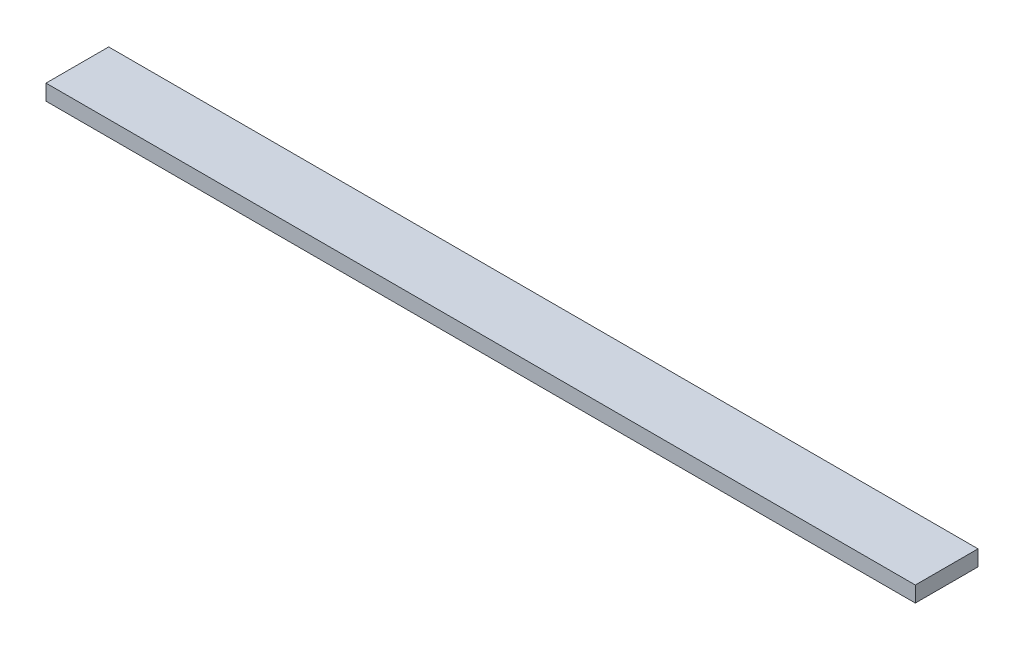
SolidWorks part; units mm, degrees
ref_plane "Front Plane" through (0, 0, 0) normal (0, 0, 1) x (1, 0, 0)
ref_plane "Top Plane" through (0, 0, 0) normal (0, 1, 0) x (1, 0, 0)
ref_plane "Right Plane" through (0, 0, 0) normal (1, 0, 0) x (0, 0, -1)
sketch "Sketch1" plane through (0, 0, 0) normal (0, 1, 0) x (1, 0, 0)
  line L1 (-88.0745, 6.35) -> (88.0745, 6.35)
  line L2 (-88.0745, 6.35) -> (-88.0745, -6.35)
  line L3 (-88.0745, -6.35) -> (88.0745, -6.35)
  line L4 (88.0745, 6.35) -> (88.0745, -6.35)
  point P4 (0, 6.35)
  point P5 (88.0745, 0)
  dimension "D1" = 12.7
  dimension "D2" = 176.149
extrude "Boss-Extrude1" add sketch "Sketch1" along normal blind 3.175
